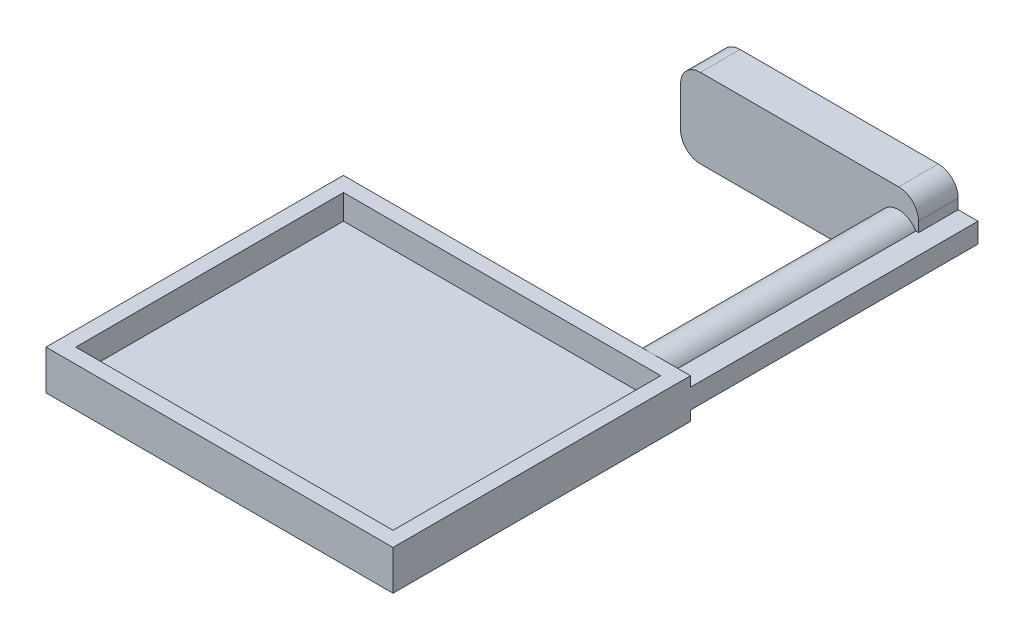
SolidWorks part; units mm, degrees
ref_plane "正面" through (0, 0, 0) normal (0, 0, 1) x (1, 0, 0)
ref_plane "平面" through (0, 0, 0) normal (0, 1, 0) x (1, 0, 0)
ref_plane "右側面" through (0, 0, 0) normal (1, 0, 0) x (0, 0, -1)
sketch "ｽｹｯﾁ1" plane through (0, 0, 0) normal (0, 0, 1) x (1, 0, 0)
  line L0 (3.4641, 2) -> (8, 2)
  line L1 (8, 2) -> (8, -2)
  line L2 (8, -2) -> (3.4641, -2)
  arc A1 (3.4641, 2) -> (3.4641, -2) centre (0, 0) ccw
  point P4 (8, 0)
  dimension "D1" = 4
  dimension "D2" = 4
  dimension "D3" = 8
extrude "ﾎﾞｽ - 押し出し1" add sketch "ｽｹｯﾁ1" against normal blind 50 and the other way blind 5
sketch "ｽｹｯﾁ2" plane through (0, 0, -50) normal (0, 0, -1) x (-1, 0, 0)
  circle A0 centre (0, 0) radius 2.1
  dimension "D1" = 4.2
sketch "ｽｹｯﾁ13" plane through (0, 0, 5) normal (0, 0, 1) x (1, 0, 0)
  circle A0 centre (0, 0) radius 8.4706
extrude "ｶｯﾄ - 押し出し6" cut sketch "ｽｹｯﾁ13" against normal blind 5
sketch "ｽｹｯﾁ23" plane through (0, 0, -50) normal (0, 0, -1) x (-1, 0, 0)
  line L0 (-4, 4) -> (-4, -4)
  line L1 (0, 8) -> (40, 8)
  line L2 (44, 4) -> (44, -4)
  line L3 (0, -8) -> (40, -8)
  line L4 (-4, 4) -> (-4, 8) construction
  line L5 (-4, 8) -> (0, 8) construction
  line L6 (40, 8) -> (44, 8) construction
  line L7 (44, 8) -> (44, 4) construction
  line L8 (44, -4) -> (44, -8) construction
  line L9 (44, -8) -> (40, -8) construction
  line L10 (0, -8) -> (-4, -8) construction
  line L11 (-4, -8) -> (-4, -4) construction
  arc A0 (-4, -4) -> (0, -8) centre (0, -4) ccw
  arc A1 (-4, 4) -> (0, 8) centre (0, 4) cw
  arc A2 (44, 4) -> (40, 8) centre (40, 4) ccw
  arc A3 (40, -8) -> (44, -4) centre (40, -4) ccw
  arc A4 (-3.4641, -2) -> (-3.4641, 2) centre (0, 0) ccw construction
  point P20 (44, 0)
  dimension "D1" = 4
  dimension "D2" = 40
  dimension "D3" = 16
extrude "ﾎﾞｽ - 押し出し7" add sketch "ｽｹｯﾁ23" along normal blind 8
sketch "ｽｹｯﾁ27" plane through (0, 0, -50) normal (0, 0, -1) x (-1, 0, 0)
  line L1 (-4, 2) -> (-8, 2)
  line L2 (-4, 2) -> (-4, -2)
  line L3 (-4, -2) -> (-8, -2)
  line L4 (-8, 2) -> (-8, -2)
extrude "ﾎﾞｽ - 押し出し9" add sketch "ｽｹｯﾁ27" along normal up to surface (8 mm away) up to face at (-20, 0, -58)
sketch "ｽｹｯﾁ24" plane through (0, 0, -58) normal (0, 0, -1) x (-1, 0, 0)
  line L0 (0, 4) -> (10, 4) construction
  line L1 (10, 4) -> (20, 4) construction
  line L2 (20, 4) -> (30, 4) construction
  line L3 (30, 4) -> (40, 4) construction
  line L4 (0, -4) -> (10, -4) construction
  line L5 (10, -4) -> (20, -4) construction
  line L6 (20, -4) -> (30, -4) construction
  line L7 (30, -4) -> (40, -4) construction
  circle A0 centre (0, 4) radius 3.2
  arc A1 (0, 8) -> (-4, 4) centre (0, 4) ccw construction
  circle A2 centre (40, 4) radius 3.2
  circle A3 centre (40, -4) radius 3.2
  circle A4 centre (0, -4) radius 3.2
  circle A5 centre (10, 4) radius 3.2
  circle A6 centre (20, 4) radius 3.2
  circle A7 centre (30, 4) radius 3.2
  circle A8 centre (10, -4) radius 3.2
  circle A9 centre (20, -4) radius 3.2
  circle A10 centre (30, -4) radius 3.2
  arc A11 (-4, -4) -> (0, -8) centre (0, -4) ccw construction
  arc A12 (40, -8) -> (44, -4) centre (40, -4) ccw construction
  arc A13 (44, 4) -> (40, 8) centre (40, 4) ccw construction
  dimension "D1" = 6.4
extrude "ｶｯﾄ - 押し出し9" cut sketch "ｽｹｯﾁ24" against normal blind 3.05
sketch "ｽｹｯﾁ25" plane through (0, 0, 0) normal (0, 0, 1) x (1, 0, 0)
  line L0 (8, -2) -> (8, 2) construction
  line L1 (8, 4) -> (-62, 4)
  line L2 (8, 4) -> (8, -4)
  line L3 (8, -4) -> (-62, -4)
  line L4 (-62, 4) -> (-62, -4)
  arc A0 (3.4641, 2) -> (3.4641, -2) centre (0, 0) ccw construction
  dimension "D1" = 70
sketch "ｽｹｯﾁ21" plane through (0, 0, 0) normal (0, 0, 1) x (1, 0, 0)
  line L1 (8, 4) -> (-62, 4)
  line L2 (8, 4) -> (8, -4)
  line L3 (8, -4) -> (-62, -4)
  line L4 (-62, 4) -> (-62, -4)
  line L5 (8, -2) -> (8, 2) construction
  arc A0 (3.4641, 2) -> (3.4641, -2) centre (0, 0) ccw construction
  dimension "D1" = 70
extrude "ﾎﾞｽ - 押し出し6" add sketch "ｽｹｯﾁ21" along normal blind 60
sketch "ｽｹｯﾁ22" plane through (0, 4, 0) normal (0, 1, 0) x (1, 0, 0)
  line L1 (5, -3) -> (-59, -3)
  line L2 (5, -3) -> (5, -57)
  line L3 (5, -57) -> (-59, -57)
  line L4 (-59, -3) -> (-59, -57)
  line L6 (-62, -60) -> (-62, 0) construction
  line L7 (8, -60) -> (8, 0) construction
  line L8 (0, 0) -> (-62, 0) construction
  line L9 (8, -60) -> (-62, -60) construction
  dimension "D1" = 3
  dimension "D2" = 3
  dimension "D3" = 3
  dimension "D4" = 3
extrude "ｶｯﾄ - 押し出し8" cut sketch "ｽｹｯﾁ22" against normal blind 5
